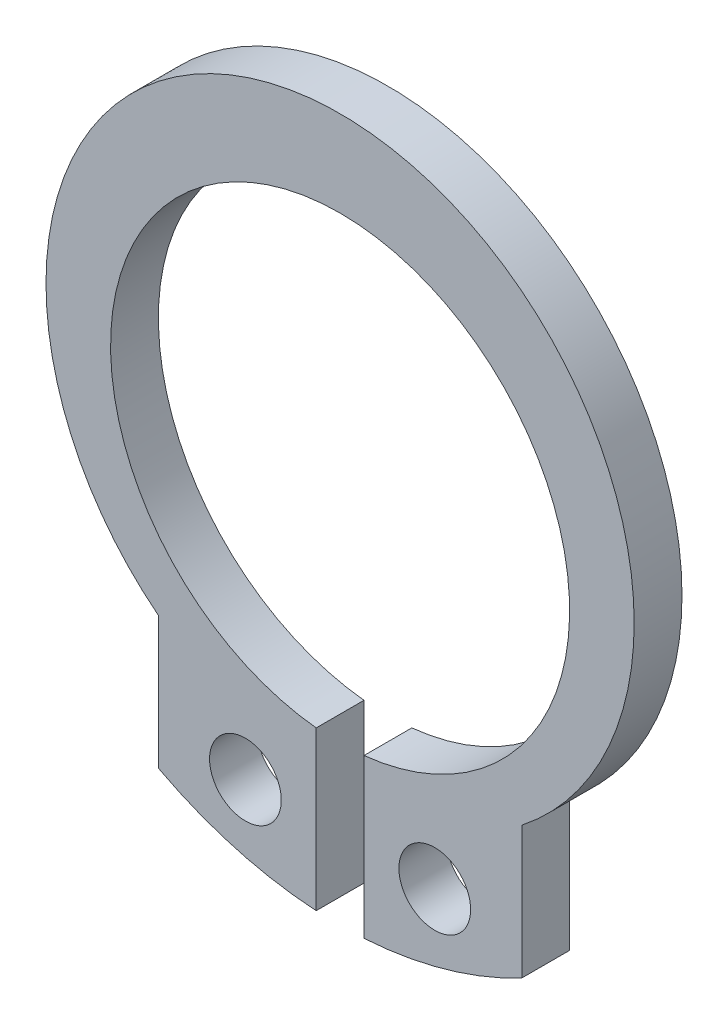
SolidWorks part; units mm, degrees
ref_plane "Ebene vorne" through (0, 0, 0) normal (0, 0, 1) x (1, 0, 0)
ref_plane "Ebene oben" through (0, 0, 0) normal (0, 1, 0) x (1, 0, 0)
ref_plane "Ebene rechts" through (0, 0, 0) normal (1, 0, 0) x (0, 0, -1)
ref_plane "Ebene1" through (0, 0, 1) normal (0, 0, 1) x (1, 0, 0)
sketch "Skizze1" plane through (0, 0, 1) normal (0, 0, 1) x (1, 0, 0)
  line L0 (-0.5, -8.0846) -> (-0.5, -4.7739)
  line L1 (0.5, -4.7739) -> (0.5, -8.0846)
  line L2 (3.8, -7.1533) -> (3.8, -4.3855)
  line L3 (-3.8, -4.3855) -> (-3.8, -7.1533)
  circle A0 centre (1.98, -6.45) radius 0.75
  circle A1 centre (-1.98, -6.45) radius 0.75
  arc A2 (-0.5, -4.7739) -> (0.5, -4.7739) centre (0, 0) cw
  arc A3 (0.5, -8.0846) -> (3.8, -7.1533) centre (0, 0) ccw
  arc A4 (3.8, -4.3855) -> (-3.8, -4.3855) centre (0, 0.45) ccw
  arc A5 (-3.8, -7.1533) -> (-0.5, -8.0846) centre (0, 0) ccw
extrude "Aufsatz-Linear austragen1" add sketch "Skizze1" against normal blind 1
